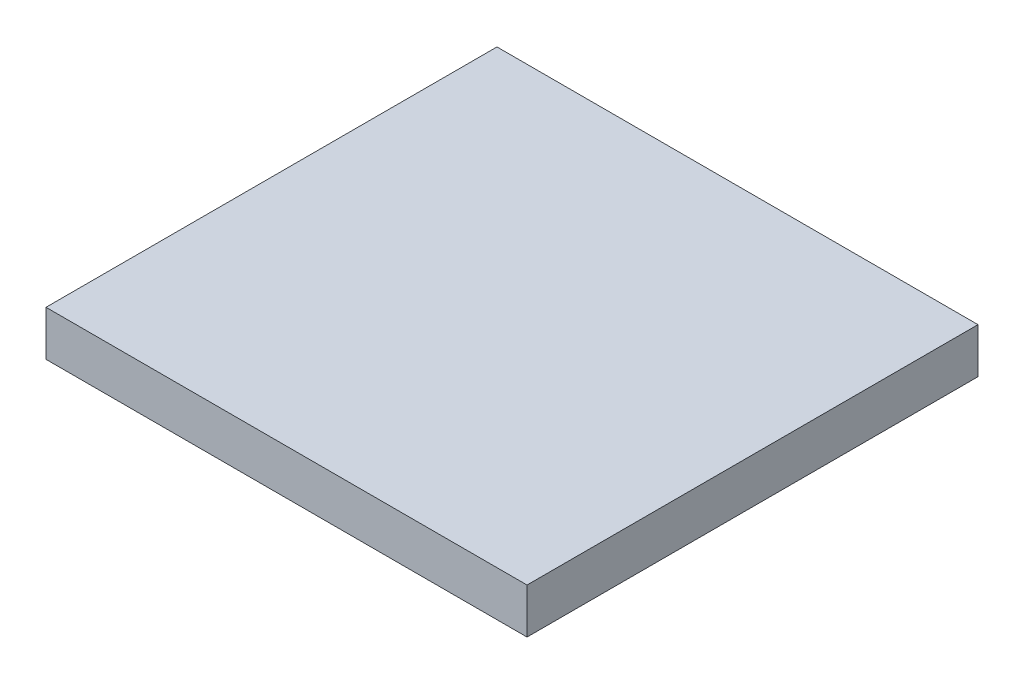
SolidWorks part; units mm, degrees
ref_plane "Plan de face" through (0, 0, 0) normal (0, 0, 1) x (1, 0, 0)
ref_plane "Plan de dessus" through (0, 0, 0) normal (0, 1, 0) x (1, 0, 0)
ref_plane "Plan de droite" through (0, 0, 0) normal (1, 0, 0) x (0, 0, -1)
sketch "Sketch2" plane through (0, 0, 0) normal (0, 1, 0) x (1, 0, 0)
  line L1 (80, -75) -> (-80, -75)
  line L2 (80, -75) -> (80, 75)
  line L3 (80, 75) -> (-80, 75)
  line L4 (-80, -75) -> (-80, 75)
  line L5 (80, -75) -> (-80, 75) construction
  line L6 (80, 75) -> (-80, -75) construction
  point P0 (0, 0)
  dimension "D1" = 150
  dimension "D2" = 160
extrude "Boss-Extrude1" add sketch "Sketch2" along normal blind 15
